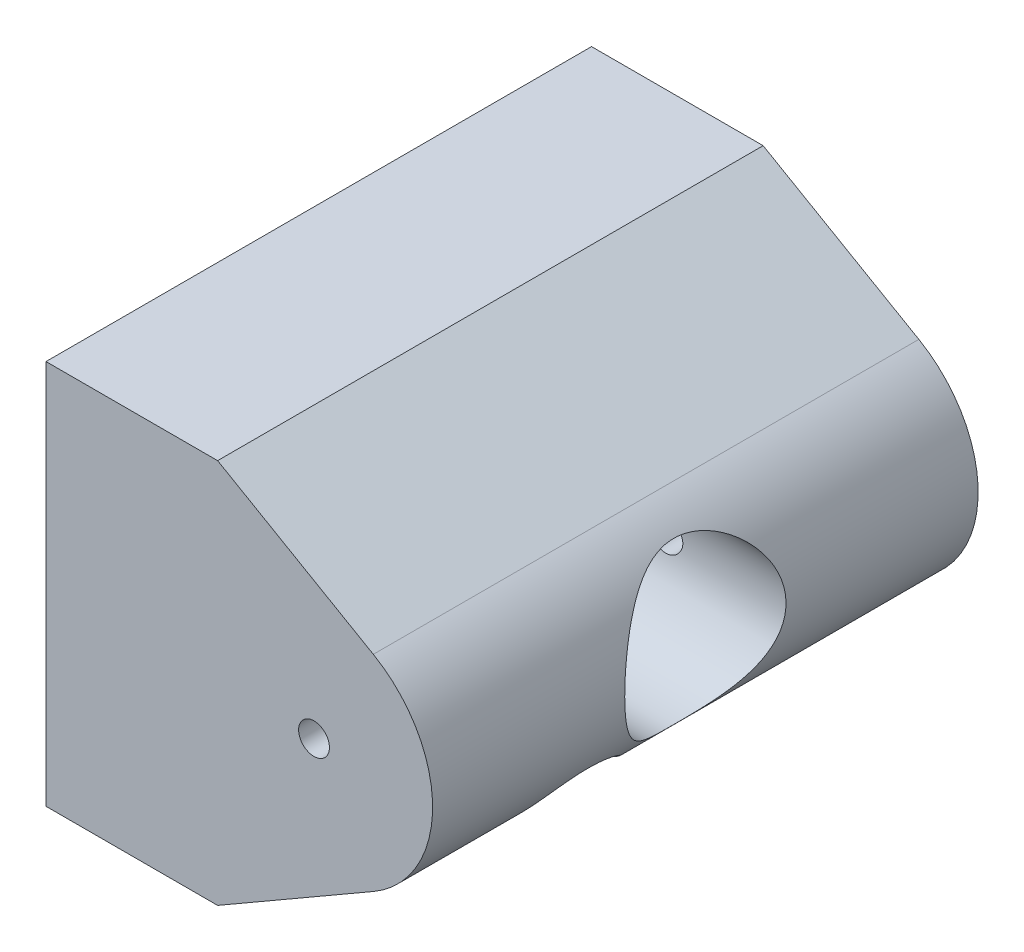
SolidWorks part; units mm, degrees
ref_plane "Plan de face" through (0, 0, 0) normal (0, 0, 1) x (1, 0, 0)
ref_plane "Plan de dessus" through (0, 0, 0) normal (0, 1, 0) x (1, 0, 0)
ref_plane "Plan de droite" through (0, 0, 0) normal (1, 0, 0) x (0, 0, -1)
sketch "Esquisse2" plane through (0, 0, 0) normal (0, 0, 1) x (1, 0, 0)
  line L0 (-56.5, 40.6) -> (-56.5, -40.6)
  line L1 (-56.5, 40.6) -> (-20.3213, 40.6)
  line L2 (-56.5, -40.6) -> (-20.3213, -40.6)
  line L3 (-20.3213, -40.6) -> (12.5, -21.6506)
  line L4 (-20.3213, 40.6) -> (12.5, 21.6506)
  line L5 (0, 0) -> (-56.5, 0) construction
  arc A0 (12.5, 21.6506) -> (12.5, -21.6506) centre (0, 0) cw
  circle A1 centre (0, 0) radius 3.25
  dimension "D4" = 30
  dimension "D3" = 25
  dimension "D5" = 6.5
  dimension "D1" = 81.2
  dimension "D2" = 30
  dimension "D6" = 56.5
extrude "Extrusion1" add sketch "Esquisse2" along normal mid plane 115
sketch "Esquisse5" plane through (-56.5, 0, 0) normal (-1, 0, 0) x (0, 0, 1)
  line L0 (7.3, -40.6) -> (7.3, -26.7)
  line L1 (57.5, -40.6) -> (-57.5, -40.6) construction
  line L2 (35.1, -40.6) -> (7.3, -40.6)
  line L4 (35.1, -40.6) -> (35.1, -26.7)
  circle A0 centre (0, 0) radius 17
  arc A1 (7.3, -26.7) -> (35.1, -26.7) centre (21.2, -26.7) cw
  dimension "D1" = 13.9
  dimension "D6" = 34
  dimension "D2" = 13.9
  dimension "D3" = 27.8
  dimension "D4" = 13.9
  dimension "D5" = 22.4
extrude "Extrusion3" cut sketch "Esquisse5" against normal through all
